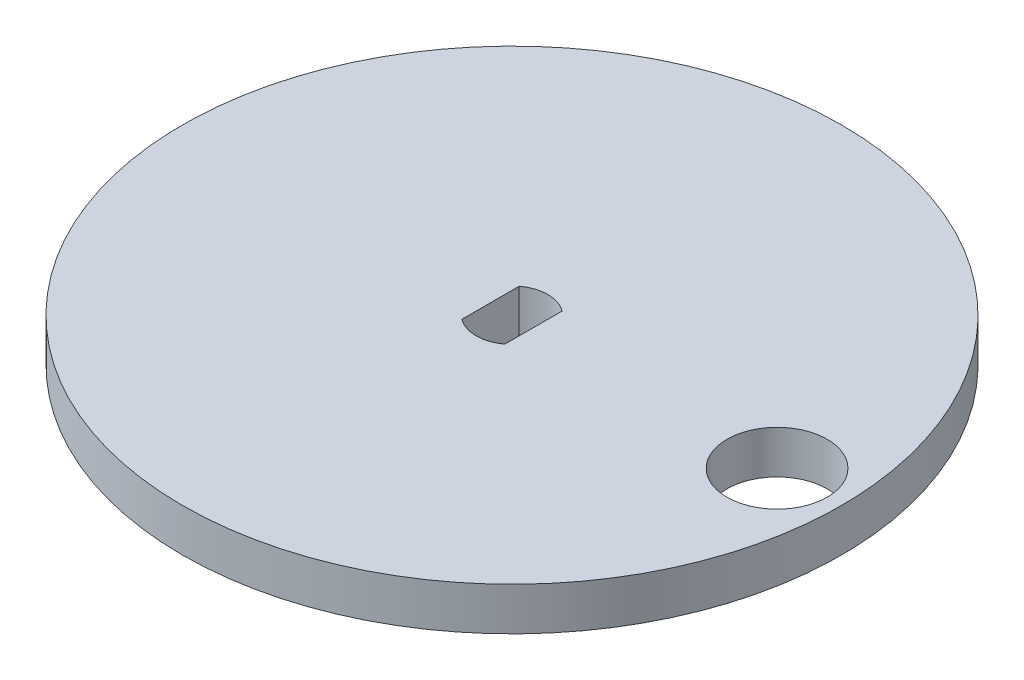
SolidWorks part; units mm, degrees
ref_plane "Alzado" through (0, 0, 0) normal (0, 0, 1) x (1, 0, 0)
ref_plane "Planta" through (0, 0, 0) normal (0, 1, 0) x (1, 0, 0)
ref_plane "Vista lateral" through (0, 0, 0) normal (1, 0, 0) x (0, 0, -1)
sketch "Croquis1" plane through (0, 0, 0) normal (0, 1, 0) x (1, 0, 0)
  line L0 (1.5, 0) -> (-1.5, 0)
  line L1 (-1.5, 0) -> (-1.5, 2)
  line L2 (-1.5, 0) -> (-1.5, -2)
  line L4 (1.5, 0) -> (1.5, -2)
  line L5 (1.5, 0) -> (1.5, 2)
  line L33 (0, 0) -> (18.5, 0) construction
  arc A0 (-1.5, -2) -> (1.5, -2) centre (0, 0) ccw
  circle A1 centre (0, 0) radius 3 construction
  circle A2 centre (0, 0) radius 23
  circle A3 centre (18.5, 0) radius 3.5
  arc A4 (1.5, 2) -> (-1.5, 2) centre (0, 0) ccw
  point P27 (0, 0)
  dimension "D2" = 1.5
  dimension "D12" = 7
  dimension "D3" = 5
  dimension "D13" = 18.5
extrude "Saliente-Extruir1" add sketch "Croquis1" along normal blind 3
